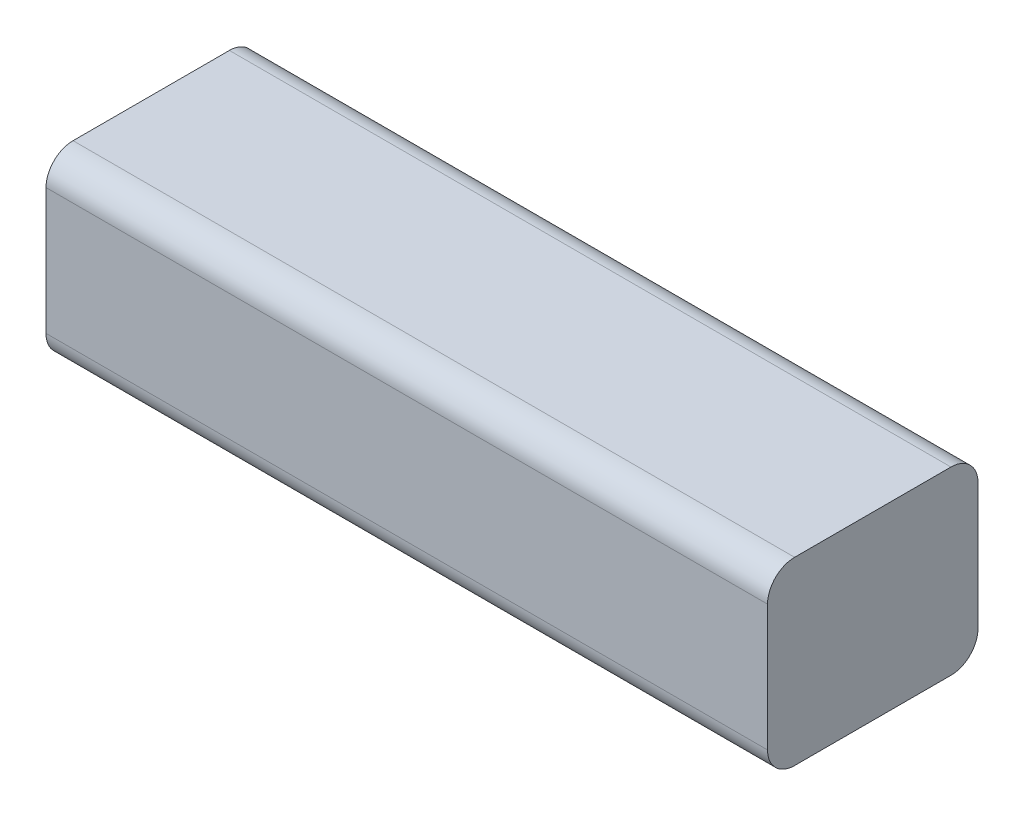
SolidWorks part; units mm, degrees
ref_plane "Front Plane" through (0, 0, 0) normal (0, 0, 1) x (1, 0, 0)
ref_plane "Top Plane" through (0, 0, 0) normal (0, 1, 0) x (1, 0, 0)
ref_plane "Right Plane" through (0, 0, 0) normal (1, 0, 0) x (0, 0, -1)
sketch "Sketch1" plane through (0, 0, 0) normal (0, 0, 1) x (1, 0, 0)
  line L0 (0, 0) -> (0, 30)
  line L1 (0, 30) -> (120, 30)
  line L2 (120, 30) -> (120, 0)
  line L3 (120, 0) -> (0, 0)
  dimension "D1" = 120
  dimension "D2" = 30
extrude "Boss-Extrude2" add sketch "Sketch1" along normal blind 35
fillet "Fillet2" radius 4.5 4 edges at (60, 0, 35) (60, 0, 0) (60, 30, 0) (60, 30, 35)
sketch "Sketch4" plane through (0, 30, 0) normal (0, 1, 0) x (1, 0, 0)
  line L0 (78.0862, 24.4054) -> (389.4195, 24.4054) construction
